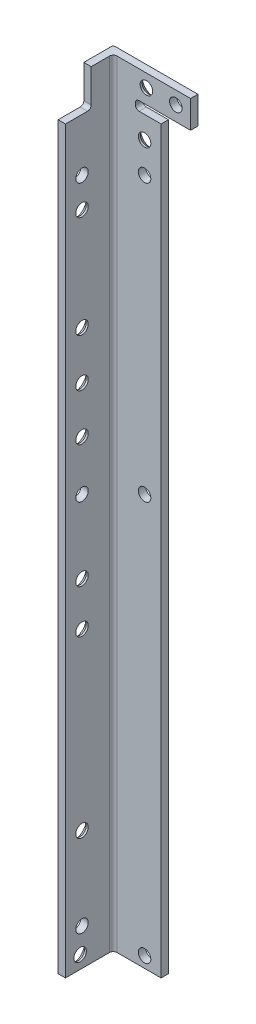
SolidWorks part; units mm, degrees
material "6061-T6 (SS)"
ref_plane "Front Plane" through (0, 0, 0) normal (0, 0, 1) x (1, 0, 0)
ref_plane "Top Plane" through (0, 0, 0) normal (0, 1, 0) x (1, 0, 0)
ref_plane "Right Plane" through (0, 0, 0) normal (1, 0, 0) x (0, 0, -1)
sketch "Sketch1" plane through (0, 0, 0) normal (0, 1, 0) x (1, 0, 0)
  line L1 (0, 0) -> (15, 0)
  line L2 (0, 0) -> (0, 15)
  line L3 (0, 15) -> (15, 15)
  line L4 (15, 0) -> (15, 15)
  line L5 (15, 0) -> (2, 0)
  line L6 (15, 0) -> (15, 13)
  line L7 (15, 13) -> (2, 13)
  line L8 (2, 0) -> (2, 13)
  dimension "D1" = 15
  dimension "D2" = 15
  dimension "D3" = 2
  dimension "D4" = 2
extrude "Boss-Extrude1" add sketch "Sketch1" along normal blind 211 contours L1 L8 L7 L4 L3 L2
sketch "Sketch16" plane through (0, 0, 0) normal (0, 0, 1) x (1, 0, 0)
  line L1 (-50, 211) -> (50, 211)
  circle A7 centre (-39.5, 32.4517) radius 1.6
  circle A8 centre (-39.5, 69.1207) radius 1.55
  circle A9 centre (-39.5, 92.7207) radius 1.55
  circle A10 centre (-39.5, 125.1207) radius 1.6
  circle A11 centre (-39.5, 137.8117) radius 1.55
  circle A12 centre (-39.5, 150.8117) radius 1.55
  circle A13 centre (-39.5, 178.5483) radius 1.55
sketch "Sketch2" plane through (0, 0, 0) normal (-1, 0, 0) x (0, 0, 1)
  line L0 (-4.5, 211) -> (22.285, 211)
  line L1 (0, 211) -> (-15, 211) construction
  line L2 (119.8363, 186.2529) -> (219.8363, 186.2529)
  line L4 (0, 211) -> (0, 0) construction
  circle A7 centre (-4.5, 32.4507) radius 1.6
  circle A8 centre (-4.5, 79.8607) radius 1.6
  circle A9 centre (-4.5, 103.4607) radius 1.6
  circle A10 centre (-4.5, 125.1207) radius 1.6
  circle A11 centre (-4.5, 137.8117) radius 1.6
  circle A12 centre (-4.5, 150.8117) radius 1.6
  circle A13 centre (-4.5, 178.5483) radius 1.6
  circle A21 centre (130.3363, 7.7046) radius 1.6
  circle A22 centre (130.3363, 44.3736) radius 1.55
  circle A23 centre (130.3363, 67.9736) radius 1.55
  circle A24 centre (130.3363, 100.3736) radius 1.6
  circle A25 centre (130.3363, 113.0646) radius 1.55
  circle A26 centre (130.3363, 126.0646) radius 1.55
  circle A27 centre (130.3363, 153.8012) radius 1.55
  dimension "D1" = 32.4517
  dimension "D2" = 27.7366
  dimension "D3" = 13
  dimension "D4" = 12.691
  dimension "D5" = 21.66
  dimension "D6" = 23.6
  dimension "D7" = 26.785
  dimension "D8" = 4.5
  dimension "D9" = 27.7366
  dimension "D10" = 13
  dimension "D11" = 12.691
  dimension "D12" = 32.4
  dimension "D13" = 23.6
  dimension "D14" = 36.669
  dimension "D15" = 32.4517
  dimension "D17" = 47.41
hole_wizard "CSK for M3 Flat Head Machine Screw1" positions "Sketch5" profile "Sketch6" countersink size "M3" standard "ANSI Metric" end condition through all
sketch "Sketch5" plane through (0, 0, 0) normal (-1, 0, 0) x (0, 0, 1)
  line L3 (0, 87.589) -> (-9, 87.589) construction
  point P0 (-4.5, 178.5483)
  point P3 (-4.5, 150.8117)
  point P6 (-4.5, 137.8117)
  point P9 (-4.5, 125.1207)
  point P12 (-4.5, 91.719)
  point P15 (-4.5, 79.8607)
  point P18 (-4.5, 32.4507)
  point P26 (0, 0)
  point P27 (0, 0)
  point P28 (0, 0)
  point P29 (0, 0)
  dimension "D1" = 4.13
sketch "Sketch6" plane through (0, 178.5483, -4.5) normal (0, 1, 0) x (0, 0, 1)
  line L0 (0, 0) -> (0, 15)
  line L1 (0, 15) -> (1.7, 15)
  line L2 (1.7, 15) -> (1.7, 1.45)
  line L3 (1.7, 1.45) -> (3.15, 0)
  line L5 (3.15, 0) -> (0, 0)
  line L6 (-1.7, 1.45) -> (-3.15, 0) construction
  line L11 (0, -6.35) -> (0, 107.95) construction
  dimension "Thru Hole Dia." = 3.4
  dimension "Thru Hole Depth" = 15
  dimension "Near C'Sink Dia." = 6.3
  dimension "Near C'Sink Angle" = 90
sketch "Sketch7" plane through (0, 0, 0) normal (-1, 0, 0) x (0, 0, 1)
  line L0 (0, 211) -> (0, 0) construction
  line L1 (0, 211) -> (-7, 211)
  line L2 (0, 211) -> (0, 201)
  line L3 (0, 201) -> (-7, 201)
  line L4 (-7, 211) -> (-7, 201)
  line L5 (-15, 211) -> (-15, 0) construction
  line L6 (0, 211) -> (-15, 211) construction
  dimension "D1" = 8
  dimension "D2" = 0
  dimension "D3" = 10
extrude "Cut-Extrude1" cut sketch "Sketch7" against normal through all
sketch "Sketch8" plane through (0, 0, -15) normal (0, 0, -1) x (-1, 0, 0)
  line L0 (-15, 211) -> (-15, 0) construction
  line L1 (-15, 201) -> (-8, 201)
  line L2 (-15, 201) -> (-15, 203.5)
  line L3 (-15, 203.5) -> (-8, 203.5)
  line L4 (-8, 201) -> (-8, 203.5)
  line L5 (0, 211) -> (0, 0) construction
  dimension "D1" = 8
  dimension "D2" = 2.5
extrude "Cut-Extrude2" cut sketch "Sketch8" against normal through all
sketch "Sketch9" plane through (0, 0, -15) normal (0, 0, -1) x (-1, 0, 0)
  line L0 (-15, 211) -> (-15, 203.5) construction
  line L1 (0, 211) -> (-15, 211) construction
  circle A0 centre (-11, 207.5) radius 1.929
  dimension "D1" = 4
  dimension "D2" = 3.5
hole_wizard "CSK for M3 Flat Head Machine Screw2" positions "Sketch10" profile "Sketch11" countersink size "M3" standard "ANSI Metric" end condition through all
sketch "Sketch10" plane through (0, 0, -15) normal (0, 0, -1) x (-1, 0, 0)
  line L0 (-15, 201) -> (-15, 0) construction
  line L3 (0, 211) -> (-15, 211) construction
  circle A0 centre (-10.5, 195) radius 1.7046
  point P0 (-11, 207.5)
  point P3 (-10.5, 195)
  dimension "D1" = 4.5
  dimension "D2" = 16
sketch "Sketch11" plane through (11, 207.5, -15) normal (1, 0, 0) x (0, 1, 0)
  line L0 (0, 0) -> (0, 15)
  line L1 (0, 15) -> (1.7, 15)
  line L2 (1.7, 15) -> (1.7, 1.45)
  line L3 (1.7, 1.45) -> (3.15, 0)
  line L5 (3.15, 0) -> (0, 0)
  line L6 (-1.7, 1.45) -> (-3.15, 0) construction
  line L11 (0, -6.35) -> (0, 107.95) construction
  dimension "Thru Hole Dia." = 3.4
  dimension "Thru Hole Depth" = 15
  dimension "Near C'Sink Dia." = 6.3
  dimension "Near C'Sink Angle" = 90
sketch "Sketch12" plane through (0, 0, 0) normal (-1, 0, 0) x (0, 0, 1)
  line L0 (0, 201) -> (0, 0) construction
  line L1 (0, 0) -> (-15, 0) construction
  circle A0 centre (-4, 3.5) radius 2.8066
  dimension "D1" = 4
  dimension "D2" = 3.5
hole_wizard "CSK for M3 Flat Head Machine Screw3" positions "Sketch13" profile "Sketch14" countersink size "M3" standard "ANSI Metric" end condition through all
sketch "Sketch13" plane through (0, 0, 0) normal (-1, 0, 0) x (0, 0, 1)
  point P0 (-4, 3.5)
sketch "Sketch14" plane through (0, 3.5, -4) normal (0, 1, 0) x (0, 0, 1)
  line L0 (0, 0) -> (0, 15)
  line L1 (0, 15) -> (1.7, 15)
  line L2 (1.7, 15) -> (1.7, 1.45)
  line L3 (1.7, 1.45) -> (3.15, 0)
  line L5 (3.15, 0) -> (0, 0)
  line L6 (-1.7, 1.45) -> (-3.15, 0) construction
  line L11 (0, -6.35) -> (0, 107.95) construction
  dimension "Thru Hole Dia." = 3.4
  dimension "Thru Hole Depth" = 15
  dimension "Near C'Sink Dia." = 6.3
  dimension "Near C'Sink Angle" = 90
fillet "Fillet1" radius 0.5 1 edges at (0, 105.5, -15)
fillet "Fillet2" radius 1 1 edges at (2, 105.5, -13)
fillet "Fillet3" radius 1 3 edges at (1, 201, -7) (8, 203.5, -14) (8, 201, -14)
sketch "Sketch17" plane through (0, 0, 0) normal (-1, 0, 0) x (0, 0, 1)
  line L0 (0, 0) -> (-14.5, 0) construction
  circle A0 centre (-4.5, 178.5483) radius 1.7 construction
  circle A1 centre (-4.5, 178.5483) radius 1.7
  circle A2 centre (-4.5, 186.68) radius 1.7
  circle A3 centre (-4.5, 111.59) radius 1.7
  circle A4 centre (-4.5, 10) radius 1.7
  dimension "D1" = 10
  dimension "D2" = 111.59
  dimension "D3" = 186.68
extrude "Cut-Extrude3" cut sketch "Sketch17" against normal blind 10
sketch "Sketch18" plane through (0, 0, -15) normal (0, 0, -1) x (-1, 0, 0)
  line L1 (-0.5, 0) -> (-15, 0) construction
  circle A2 centre (-10.5, 186.68) radius 1.7
  circle A3 centre (-10.5, 111.59) radius 1.7
  circle A4 centre (-10.5, 3) radius 1.7
  circle A5 centre (-10.5, 195) radius 1.7 construction
  circle A6 centre (-10.5, 195) radius 1.7
  dimension "D1" = 3
  dimension "D2" = 111.59
  dimension "D3" = 186.68
extrude "Cut-Extrude4" cut sketch "Sketch18" against normal blind 10
sketch "Sketch19" plane through (15, 0, 0) normal (1, 0, 0) x (0, 0, -1)
  line L1 (15, 211) -> (13, 211)
  line L2 (15, 211) -> (15, 203.5)
  line L3 (15, 203.5) -> (13, 203.5)
  line L4 (13, 211) -> (13, 203.5)
  dimension "D1" = 7.5
  dimension "D2" = 2
extrude "Boss-Extrude2" add sketch "Sketch19" along normal blind 8
sketch "Sketch20" plane through (0, 0, -13) normal (0, 0, 1) x (1, 0, 0)
  line L0 (23, 211) -> (3, 211) construction
  line L1 (23, 211) -> (23, 203.5) construction
  circle A0 centre (19, 207.5) radius 1.7
  dimension "D1" = 3.5
  dimension "D2" = 4
extrude "Cut-Extrude5" cut sketch "Sketch20" against normal blind 8
